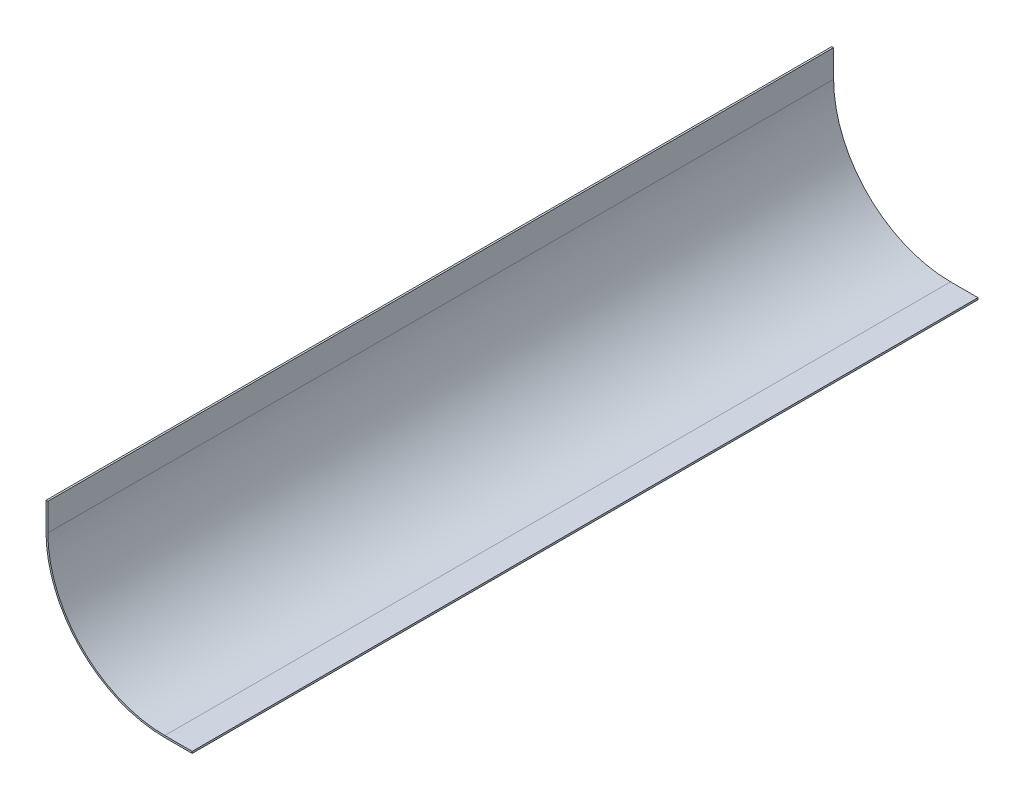
SolidWorks part; units mm, degrees
material "Acrylic (Medium-high impact)"
ref_plane "Front Plane" through (0, 0, 0) normal (0, 0, 1) x (1, 0, 0)
ref_plane "Top Plane" through (0, 0, 0) normal (0, 1, 0) x (1, 0, 0)
ref_plane "Right Plane" through (0, 0, 0) normal (1, 0, 0) x (0, 0, -1)
sketch "Sketch3" plane through (0, 0, 0) normal (0, 0, 1) x (1, 0, 0)
  line L0 (-99.8198, 73.3333) -> (-99.8198, 58.3333)
  line L1 (-34.8198, -6.6667) -> (-19.8198, -6.6667)
  line L2 (-34.8198, -5.6667) -> (-19.8198, -5.6667)
  line L3 (-98.8198, 73.3333) -> (-98.8198, 58.3333)
  line L4 (-99.8198, 73.3333) -> (-98.8198, 73.3333)
  line L5 (-19.8198, -5.6667) -> (-19.8198, -6.6667)
  arc A0 (-34.8198, -6.6667) -> (-99.8198, 58.3333) centre (-34.8198, 58.3333) cw
  arc A1 (-34.8198, -5.6667) -> (-98.8198, 58.3333) centre (-34.8198, 58.3333) cw
  point P5 (-99.8198, -6.6667)
  dimension "D3" = 65
  dimension "D1" = 80
  dimension "D2" = 80
  dimension "D4" = 1
extrude "Boss-Extrude4" add sketch "Sketch3" along normal blind 430
